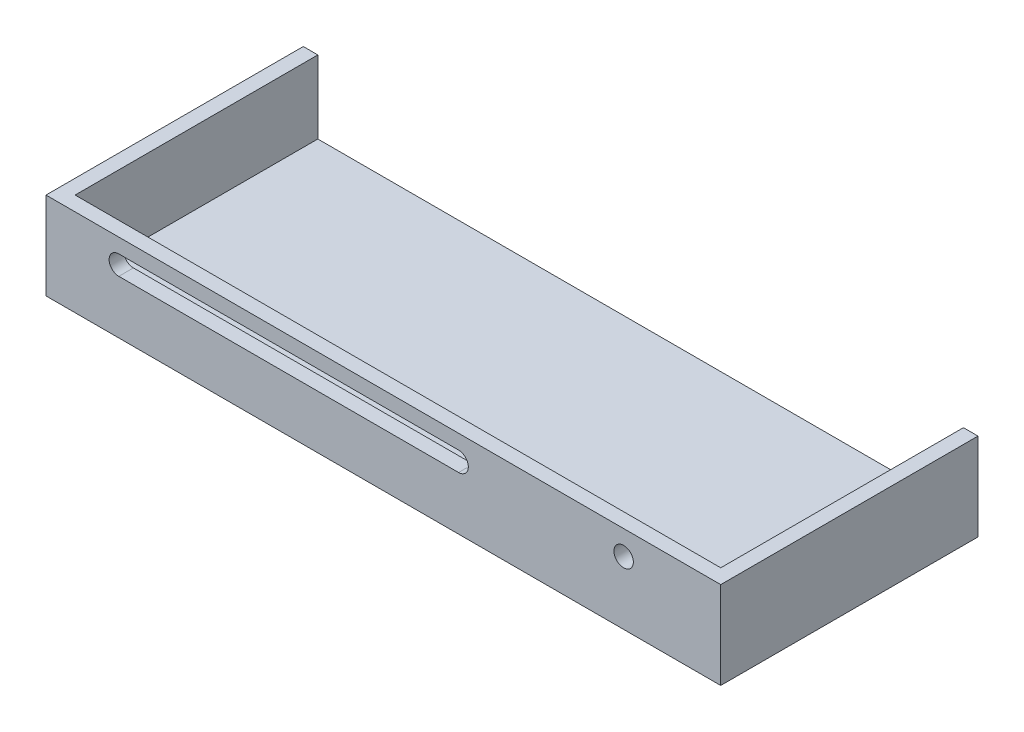
SolidWorks part; units mm, degrees
ref_plane "Front Plane" through (0, 0, 0) normal (0, 0, 1) x (1, 0, 0)
ref_plane "Top Plane" through (0, 0, 0) normal (0, 1, 0) x (1, 0, 0)
ref_plane "Right Plane" through (0, 0, 0) normal (1, 0, 0) x (0, 0, -1)
sketch "Sketch3" plane through (0, 0, 0) normal (1, 0, 0) x (0, 0, -1)
  line L0 (-34.8081, 35) -> (-34.8081, 10)
  line L2 (-37.8081, 0) -> (-37.8081, 35)
  line L3 (-37.8081, 35) -> (-34.8081, 35)
  line L4 (-19.8081, 0) -> (-19.8081, 35)
  line L5 (-34.8081, 10) -> (-22.8081, 10)
  line L6 (-22.8081, 10) -> (-22.8081, 35)
  line L7 (-22.8081, 35) -> (-19.8081, 35)
  line L18 (-29.8081, -3) -> (15.1919, -3)
  line L19 (15.1919, -3) -> (15.1919, 0)
  line L20 (15.1919, 0) -> (-19.8081, 0)
  line L21 (-37.8081, 0) -> (-37.8081, -3)
  line L22 (-29.8081, -3) -> (-37.8081, -3)
  dimension "D1" = 12
  dimension "D2" = 3
  dimension "D3" = 3
  dimension "D4" = 35
  dimension "D5" = 35
  dimension "D7" = 3
extrude "Boss-Extrude1" add sketch "Sketch3" along normal blind 139
sketch "Sketch5" plane through (0, 0, 19.8081) normal (0, 0, -1) x (-1, 0, 0)
  line L0 (-85, 30) -> (-15, 30) construction
  line L1 (-85, 32) -> (-15, 32)
  line L2 (-85, 28) -> (-15, 28)
  line L3 (-139, 0) -> (-139, 35) construction
  line L5 (0, 0) -> (0, 35) construction
  line L6 (-139, 35) -> (0, 35) construction
  circle A0 centre (-119, 30) radius 2
  arc A1 (-85, 32) -> (-85, 28) centre (-85, 30) ccw
  arc A2 (-15, 28) -> (-15, 32) centre (-15, 30) ccw
  point P2 (-50, 30)
  dimension "D1" = 4
  dimension "D2" = 4
  dimension "D3" = 20
  dimension "D4" = 5
  dimension "D5" = 15
  dimension "D6" = 70
extrude "Cut-Extrude1" cut sketch "Sketch5" against normal through all
sketch "Sketch6" plane through (0, 0, 0) normal (0, 1, 0) x (1, 0, 0)
  line L0 (139, 15.1919) -> (0, 15.1919) construction
  line L1 (0, -19.8081) -> (3, -19.8081)
  line L2 (0, -19.8081) -> (0, 15.1919)
  line L3 (0, 15.1919) -> (3, 15.1919)
  line L4 (3, -19.8081) -> (3, 15.1919)
  line L6 (139, -19.8081) -> (136, -19.8081)
  line L7 (139, -19.8081) -> (139, 15.1919)
  line L8 (139, 15.1919) -> (136, 15.1919)
  line L9 (136, -19.8081) -> (136, 15.1919)
  dimension "D1" = 3
extrude "Boss-Extrude2" add sketch "Sketch6" along normal up to surface (35 mm away) up to face at (69.5, 35, 21.3081)
sketch "Sketch7" plane through (0, 0, 19.8081) normal (0, 0, -1) x (-1, 0, 0)
  line L1 (-3, 0) -> (-136, 0)
  line L2 (-3, 0) -> (-3, 35)
  line L3 (-3, 35) -> (-136, 35)
  line L4 (-136, 0) -> (-136, 35)
extrude "Boss-Extrude3" add sketch "Sketch7" along normal blind 5
sketch "Sketch8" plane through (0, 0, 14.8081) normal (0, 0, -1) x (-1, 0, 0)
  line L1 (-136, 0) -> (-3, 0)
  line L2 (-136, 0) -> (-136, 35)
  line L3 (-136, 35) -> (-3, 35)
  line L4 (-3, 0) -> (-3, 35)
extrude "Cut-Extrude2" cut sketch "Sketch8" against normal up to surface (20 mm away) up to face at (119, 28, 34.8081)
sketch "Sketch9" plane through (0, 10, 0) normal (0, 1, 0) x (1, 0, 0)
  line L1 (139, -34.8081) -> (136, -34.8081)
  line L2 (139, -34.8081) -> (139, -22.8081)
  line L3 (139, -22.8081) -> (136, -22.8081)
  line L4 (136, -34.8081) -> (136, -22.8081)
  line L5 (0, -34.8081) -> (3, -34.8081)
  line L6 (0, -34.8081) -> (0, -22.8081)
  line L7 (0, -22.8081) -> (3, -22.8081)
  line L8 (3, -34.8081) -> (3, -22.8081)
extrude "Boss-Extrude4" add sketch "Sketch9" along normal up to surface (25 mm away) up to face at (137.5, 35, 3.8081)
sketch "Sketch10" plane through (0, 0, 0) normal (0, 1, 0) x (1, 0, 0)
  line L1 (3, -34.8081) -> (136, -34.8081)
  line L2 (3, -34.8081) -> (3, 15.1919)
  line L3 (3, 15.1919) -> (136, 15.1919)
  line L4 (136, -34.8081) -> (136, 15.1919)
extrude "Boss-Extrude5" add sketch "Sketch10" along normal blind 20
sketch "Sketch11" plane through (0, -3, 0) normal (0, -1, 0) x (1, 0, 0)
  line L1 (0, 37.8081) -> (139, 37.8081)
  line L2 (0, 37.8081) -> (0, -15.1919)
  line L3 (0, -15.1919) -> (139, -15.1919)
  line L4 (139, 37.8081) -> (139, -15.1919)
extrude "Cut-Extrude3" cut sketch "Sketch11" against normal blind 20
